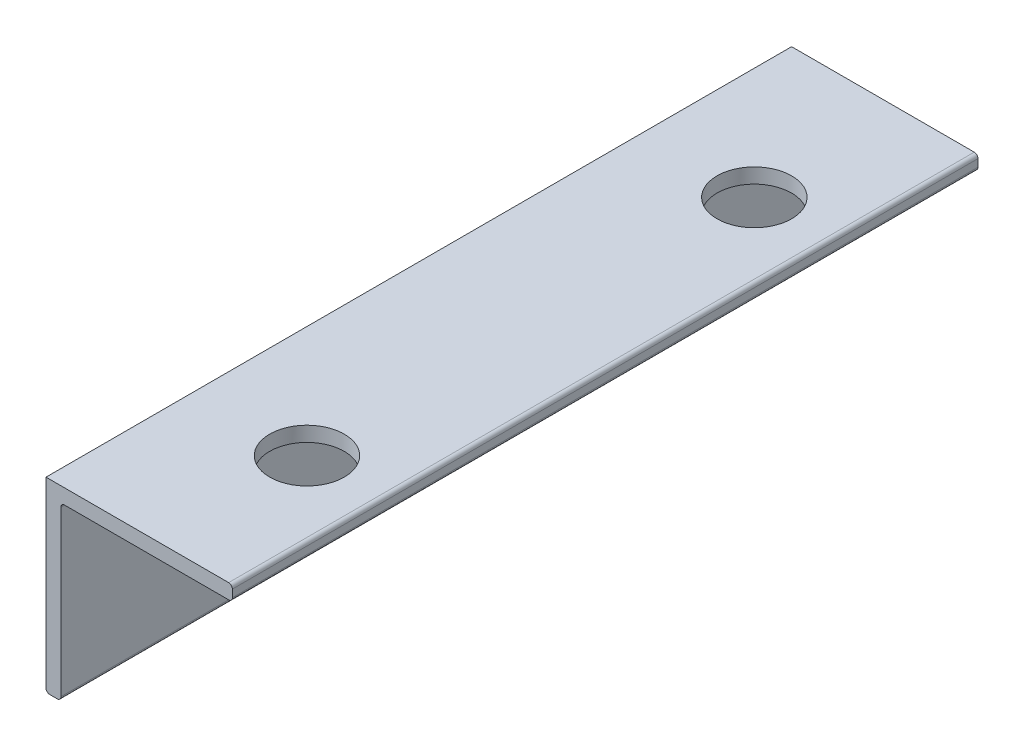
SolidWorks part; units mm, degrees
material "1060-H12"
ref_plane "Спереди" through (0, 0, 0) normal (0, 0, 1) x (1, 0, 0)
ref_plane "Сверху" through (0, 0, 0) normal (0, 1, 0) x (1, 0, 0)
ref_plane "Справа" through (0, 0, 0) normal (1, 0, 0) x (0, 0, -1)
sketch "Эскиз1" plane through (0, 0, 0) normal (0, 0, 1) x (1, 0, 0)
  line L0 (10, 14.5) -> (10, 13.5)
  line L2 (-15, -9.5) -> (-15, 15)
  line L3 (-15, 15) -> (9.5, 15)
  line L5 (-15, -15) -> (15, 15) construction
  line L6 (-15, 15) -> (15, -15) construction
  line L7 (-14.5, -10) -> (-13.5, -10)
  line L8 (9.5, 13) -> (-12.5, 13)
  line L9 (-13, 12.5) -> (-13, -9.5)
  arc A0 (-13.5, -10) -> (-13, -9.5) centre (-13.5, -9.5) ccw
  arc A1 (-14.5, -10) -> (-15, -9.5) centre (-14.5, -9.5) cw
  arc A2 (10, 13.5) -> (9.5, 13) centre (9.5, 13.5) cw
  arc A3 (9.5, 15) -> (10, 14.5) centre (9.5, 14.5) cw
  arc A4 (-12.5, 13) -> (-13, 12.5) centre (-12.5, 12.5) ccw
  point P0 (0, 0)
  point P23 (-13, 13)
  dimension "D4" = 0.5
  dimension "D5" = 0.5
  dimension "D1" = 30
  dimension "D2" = 25
  dimension "D3" = 25
extrude "Бобышка-Вытянуть1" add sketch "Эскиз1" along normal blind 100
sketch "Эскиз2" plane through (0, 15, 0) normal (0, 1, 0) x (1, 0, 0)
  line L0 (-15, -100) -> (-15, 0) construction
  line L1 (9.5, -100) -> (-15, -100) construction
  line L4 (9.5, 0) -> (-15, 0) construction
  circle A0 centre (0, -80) radius 5
  circle A1 centre (0, -20) radius 5
  point P10 (3.2982, 0)
  dimension "D1" = 10
  dimension "D4" = 10
  dimension "D2" = 20
  dimension "D3" = 15
  dimension "D5" = 15
  dimension "D6" = 20
extrude "Вырез-Вытянуть1" cut sketch "Эскиз2" against normal up to next
